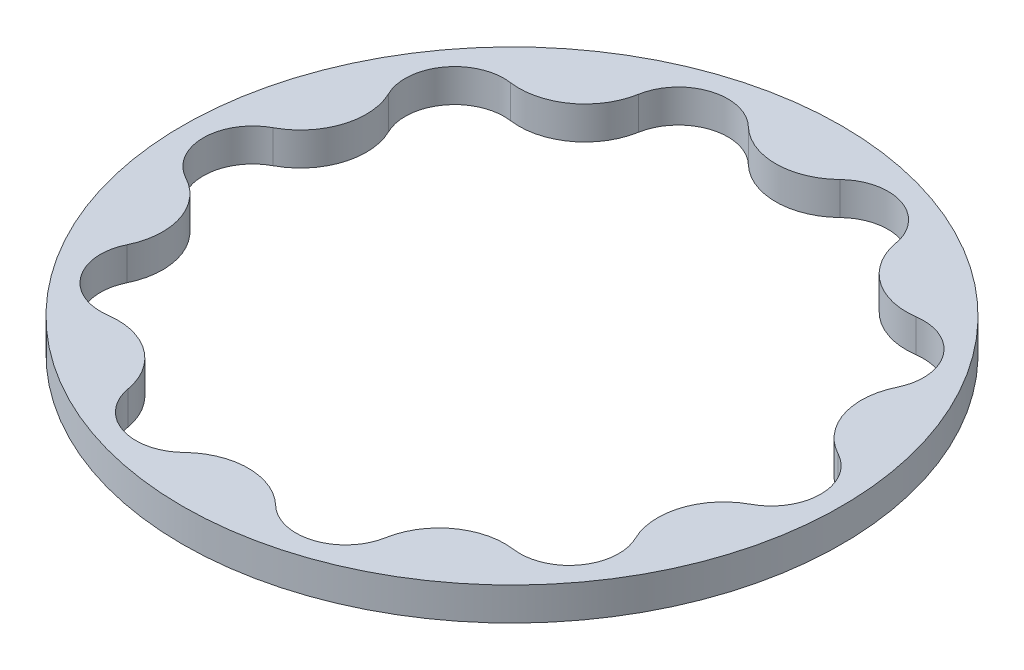
SolidWorks part; units mm, degrees
ref_plane "Front Plane" through (0, 0, 0) normal (0, 0, 1) x (1, 0, 0)
ref_plane "Top Plane" through (0, 0, 0) normal (0, 1, 0) x (1, 0, 0)
ref_plane "Right Plane" through (0, 0, 0) normal (1, 0, 0) x (0, 0, -1)
sketch "Sketch1" plane through (0, 0, 0) normal (0, 1, 0) x (1, 0, 0)
  arc A0 (-13.8919, 85.612) -> (13.8919, 85.612) centre (0, 100) ccw
  arc A1 (39.0827, 77.427) -> (61.5602, 61.0961) centre (58.7785, 80.9017) ccw
  arc A2 (77.129, 39.6675) -> (85.7146, 13.2436) centre (95.1057, 30.9017) ccw
  arc A4 (61.5602, -61.0961) -> (39.0827, -77.427) centre (58.7785, -80.9017) ccw
  arc A5 (13.8919, -85.612) -> (-13.8919, -85.612) centre (0, -100) ccw
  arc A6 (-39.0827, -77.427) -> (-61.5602, -61.0961) centre (-58.7785, -80.9017) ccw
  arc A7 (-77.129, -39.6675) -> (-85.7146, -13.2436) centre (-95.1057, -30.9017) ccw
  arc A8 (-85.7146, 13.2436) -> (-77.129, 39.6675) centre (-95.1057, 30.9017) ccw
  circle A9 centre (0, 0) radius 100
  arc A10 (-61.5602, 61.0961) -> (-39.0827, 77.427) centre (-58.7785, 80.9017) ccw
  arc A11 (13.8919, 85.612) -> (39.0827, 77.427) centre (24.3108, 74.8209) cw
  arc A12 (61.5602, 61.0961) -> (77.129, 39.6675) centre (63.6465, 46.2419) cw
  arc A13 (85.7146, 13.2436) -> (85.7146, -13.2436) centre (78.6714, 0) cw
  arc A14 (77.129, -39.6675) -> (61.5602, -61.0961) centre (63.6465, -46.2419) cw
  arc A15 (39.0827, -77.427) -> (13.8919, -85.612) centre (24.3108, -74.8209) cw
  arc A16 (-13.8919, -85.612) -> (-39.0827, -77.427) centre (-24.3108, -74.8209) cw
  arc A17 (-61.5602, -61.0961) -> (-77.129, -39.6675) centre (-63.6465, -46.2419) cw
  arc A18 (-85.7146, -13.2436) -> (-85.7146, 13.2436) centre (-78.6714, 0) cw
  arc A19 (-77.129, 39.6675) -> (-61.5602, 61.0961) centre (-63.6465, 46.2419) cw
  arc A20 (-39.0827, 77.427) -> (-13.8919, 85.612) centre (-24.3108, 74.8209) cw
  circle A21 centre (0, 0) radius 78.6714 construction
  arc A22 (85.7146, -13.2436) -> (77.129, -39.6675) centre (95.1057, -30.9017) ccw
  arc A23 (87.0542, -49.2095) -> (99.3529, -11.3579) centre (95.1057, -30.9017) ccw [skipped]
  point P24 (0, 0)
  point P30 (0, -0.1637)
  point P56 (0, 0)
  dimension "D1" = 200
  dimension "D2" = 20
  dimension "D4" = 10
  dimension "D5" = 15
  dimension "D6" = 10
extrude "Boss-Extrude1" add sketch "Sketch1" along normal blind 10 contours A8 A19 A10 A20 A0 A11 A1 A12 A2 A13 A22 A14 A4 A15 A5 A16 A6 A17 A7 A18
